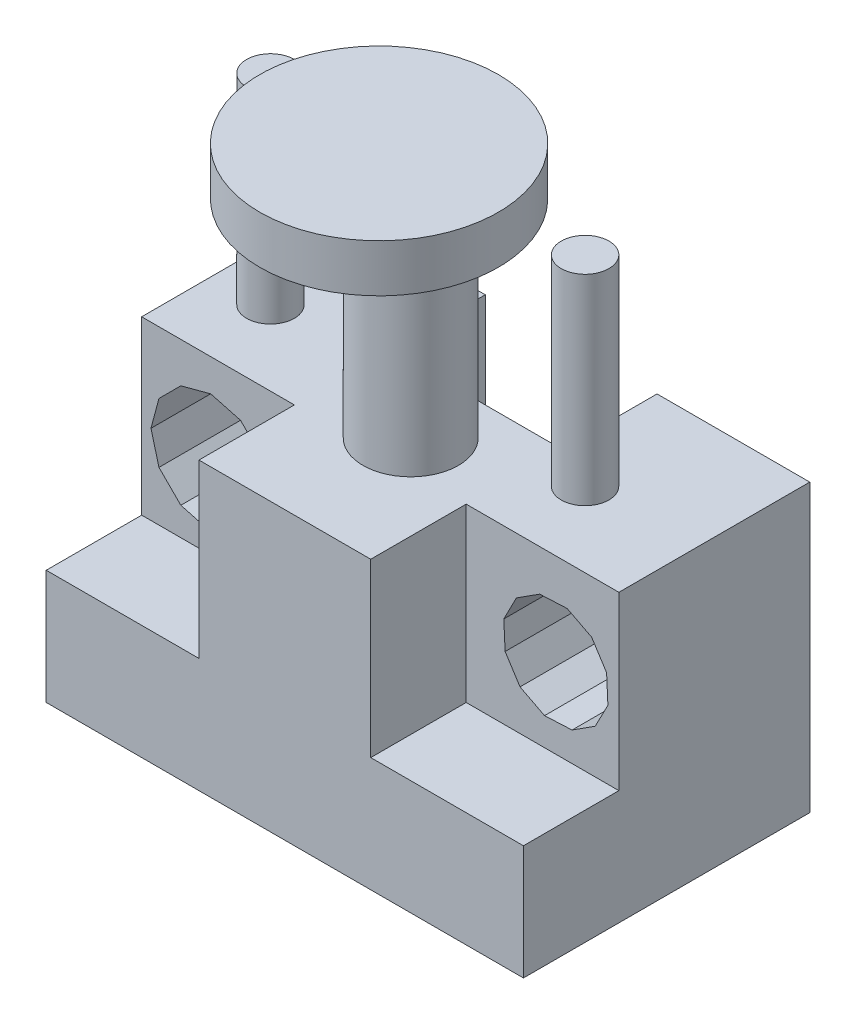
SolidWorks part; units mm, degrees
ref_plane "Front Plane" through (0, 0, 0) normal (0, 0, 1) x (1, 0, 0)
ref_plane "Top Plane" through (0, 0, 0) normal (0, 1, 0) x (1, 0, 0)
ref_plane "Right Plane" through (0, 0, 0) normal (1, 0, 0) x (0, 0, -1)
sketch "Sketch1" plane through (0, 0, 0) normal (0, 0, 1) x (1, 0, 0)
  line L1 (0, 0) -> (50000, 0)
  line L2 (0, 0) -> (0, -30000)
  line L3 (0, -30000) -> (50000, -30000)
  line L4 (50000, 0) -> (50000, -30000)
  dimension "D1" = 50000
  dimension "D2" = 30000
extrude "Boss-Extrude1" add sketch "Sketch1" along normal blind 30000
sketch "Sketch2" plane through (0, 0, 30000) normal (0, 0, 1) x (1, 0, 0)
  line L1 (0, 0) -> (16000, 0)
  line L2 (0, 0) -> (0, -18000)
  line L3 (0, -18000) -> (16000, -18000)
  line L4 (16000, 0) -> (16000, -18000)
  line L5 (50000, 0) -> (34000, 0)
  line L6 (50000, 0) -> (50000, -18000)
  line L7 (50000, -18000) -> (34000, -18000)
  line L8 (34000, 0) -> (34000, -18000)
  dimension "D1" = 16000
  dimension "D2" = 18000
  dimension "D3" = 16000
  dimension "D4" = 18000
extrude "Cut-Extrude1" cut sketch "Sketch2" against normal blind 10000
sketch "Sketch3" plane through (0, 0, 0) normal (0, 0, -1) x (-1, 0, 0)
  line L0 (-50000, 0) -> (0, 0) construction
  line L1 (-34000, 0) -> (-16000, 0)
  line L2 (-34000, 0) -> (-34000, -17072.2104)
  line L3 (-34000, -17072.2104) -> (-16000, -17072.2104)
  line L4 (-16000, 0) -> (-16000, -17072.2104)
  line L5 (0, 0) -> (0, -30000) construction
  dimension "D1" = 18000
  dimension "D2" = 16000
extrude "Cut-Extrude2" cut sketch "Sketch3" against normal blind 10000
sketch "Sketch4" plane through (0, 0, 0) normal (0, 1, 0) x (1, 0, 0)
  circle A0 centre (25086.3421, -16899.5262) radius 5000
  dimension "D1" = 10000
extrude "Boss-Extrude2" add sketch "Sketch4" along normal blind 21000
sketch "Sketch5" plane through (0, 21000, 0) normal (0, 1, 0) x (1, 0, 0)
  circle A1 centre (22703.6918, -17829.1187) radius 12500
  dimension "D1" = 25000
extrude "Boss-Extrude3" add sketch "Sketch5" along normal blind 5000
sketch "Sketch6" plane through (0, 0, 20000) normal (0, 0, 1) x (1, 0, 0)
  line L1 (13486.6363, -9633.8607) -> (12648.322, -6505.2293)
  line L2 (12648.322, -6505.2293) -> (10358.0048, -4214.9121)
  line L3 (10358.0048, -4214.9121) -> (7229.3734, -3376.5978)
  line L4 (7229.3734, -3376.5978) -> (4100.7419, -4214.9121)
  line L5 (4100.7419, -4214.9121) -> (1810.4248, -6505.2293)
  line L6 (1810.4248, -6505.2293) -> (972.1105, -9633.8607)
  line L7 (972.1105, -9633.8607) -> (1810.4248, -12762.4922)
  line L8 (1810.4248, -12762.4922) -> (4100.7419, -15052.8094)
  line L9 (4100.7419, -15052.8094) -> (7229.3734, -15891.1236)
  line L10 (7229.3734, -15891.1236) -> (10358.0048, -15052.8094)
  line L11 (10358.0048, -15052.8094) -> (12648.322, -12762.4922)
  line L12 (12648.322, -12762.4922) -> (13486.6363, -9633.8607)
  circle A0 centre (7229.3734, -9633.8607) radius 6044.0518 construction
extrude "Cut-Extrude3" cut sketch "Sketch6" against normal blind 10000
sketch "Sketch7" plane through (0, 0, 20000) normal (0, 0, 1) x (1, 0, 0)
  line L1 (39266.5594, -5879.503) -> (37942.6679, -8447.3883)
  line L2 (37942.6679, -8447.3883) -> (38080.087, -11333.188)
  line L3 (38080.087, -11333.188) -> (39641.9952, -13763.6542)
  line L4 (39641.9952, -13763.6542) -> (42209.8805, -15087.5457)
  line L5 (42209.8805, -15087.5457) -> (45095.6801, -14950.1267)
  line L6 (45095.6801, -14950.1267) -> (47526.1464, -13388.2185)
  line L7 (47526.1464, -13388.2185) -> (48850.0379, -10820.3332)
  line L8 (48850.0379, -10820.3332) -> (48712.6188, -7934.5335)
  line L9 (48712.6188, -7934.5335) -> (47150.7106, -5504.0672)
  line L10 (47150.7106, -5504.0672) -> (44582.8253, -4180.1758)
  line L11 (44582.8253, -4180.1758) -> (41697.0257, -4317.5948)
  line L12 (41697.0257, -4317.5948) -> (39266.5594, -5879.503)
  circle A0 centre (43396.3529, -9633.8607) radius 5391.0774 construction
extrude "Cut-Extrude4" cut sketch "Sketch7" against normal blind 10000
sketch "Sketch8" plane through (0, 0, 0) normal (0, 1, 0) x (1, 0, 0)
  circle A0 centre (38607.2227, -12149.5425) radius 2500
  circle A1 centre (5644.669, -12149.5425) radius 2500
  dimension "D1" = 5000
  dimension "D2" = 5000
extrude "Boss-Extrude4" add sketch "Sketch8" along normal blind 21000
sketch "Sketch9" plane through (0, 26000, 0) normal (0, 1, 0) x (1, 0, 0)
